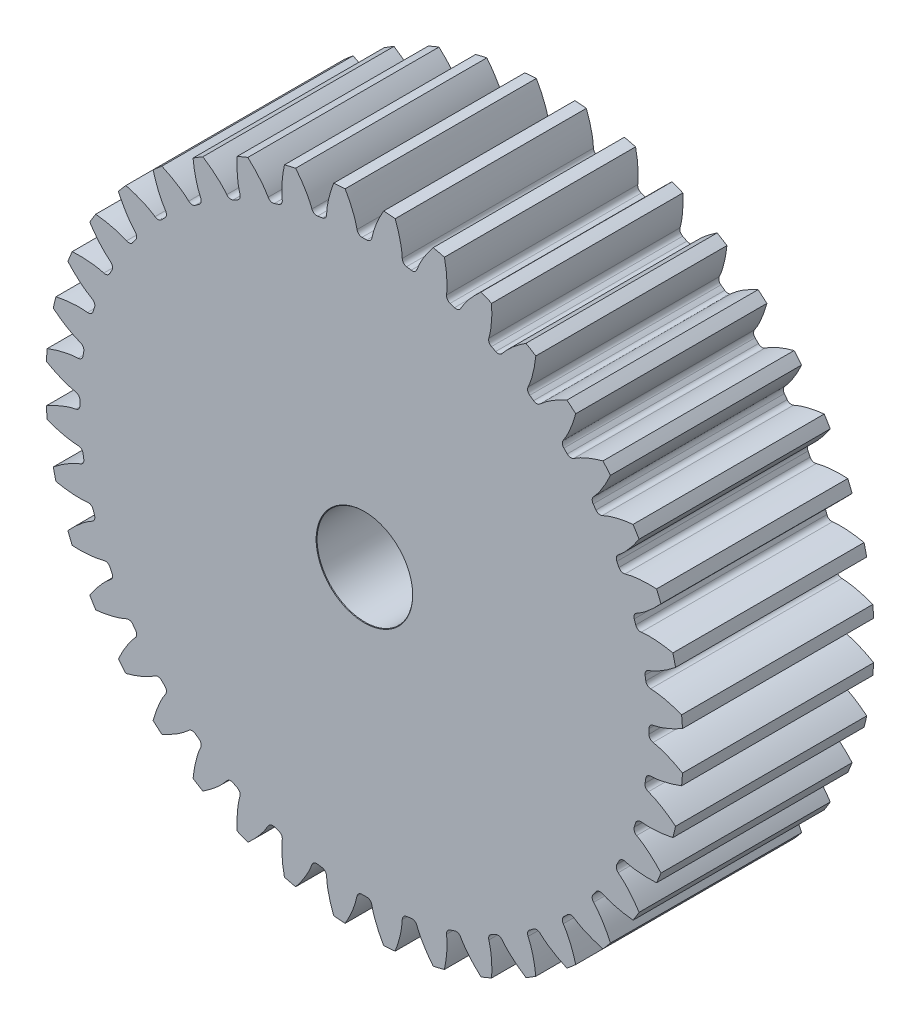
SolidWorks part; units mm, degrees
ref_plane "Front Plane" through (0, 0, 0) normal (0, 0, 1) x (1, 0, 0)
ref_plane "Top Plane" through (0, 0, 0) normal (0, 1, 0) x (1, 0, 0)
ref_plane "Right Plane" through (0, 0, 0) normal (1, 0, 0) x (0, 0, -1)
sketch "Sketch1" plane through (0, 0, 0) normal (0, 0, 1) x (1, 0, 0)
  line L0 (0, 0) -> (0, 15.875) construction
  line L1 (-5.1021, 17.732) -> (5.1021, 14.018) construction
  circle A0 centre (0, 0) radius 14.8828 construction
  circle A1 centre (0, 0) radius 16.6687 construction
  circle A2 centre (0, 0) radius 15.875 construction
  circle A3 centre (0, 0) radius 14.9176 construction
  point P8 (406.4, 0)
  point P13 (508, 0)
  dimension "OD | Outside Diameter" = 33.3375
  dimension "Root Diameter" = 29.7656
  dimension "Gear Pitch Diameter" = 31.75
  dimension "Base Diameter" = 29.8352
  dimension "Pressure Angle" = 20
  dimension "Number of Teeth" = 1016
  dimension "Gear Pitch | Diametral Pitch" = 812.8
sketch "Sketch2" plane through (0, 0, 0) normal (1, 0, 0) x (0, 0, -1)
  line L0 (-5, 0) -> (5, 0) construction
  point P2 (11.6687, 0)
  point P5 (20.0031, 0)
  point P6 (-11.6687, 0)
  dimension "Length" = 10
  dimension "D1" = 16.6687
  dimension "D2" = 25.0031
  dimension "D3" = 16.6687
sketch "Sketch3" plane through (0, 0, 0) normal (0, 0, 1) x (1, 0, 0)
  circle A0 centre (0, 0) radius 16.6687
  circle A1 centre (0, 0) radius 16.6687 construction
extrude "Boss-Extrude1" add sketch "Sketch3" against normal up to vertex (5 mm away) and the other way up to vertex (5 mm away) up to point (0, 0, -5) other way up to point (0, 0, 5)
sketch "Sketch4" plane through (0, 0, 0) normal (0, 0, 1) x (1, 0, 0)
  line L0 (0, 0) -> (14.8784, 0.3626) construction
  line L2 (0, 0) -> (14.8784, -0.3626) construction
  line L4 (14.8784, 0.3626) -> (14.9132, 0.3634)
  line L5 (14.9132, -0.3634) -> (14.8784, -0.3626)
  arc A0 (14.8784, 0.3626) -> (14.8784, -0.3626) centre (0, 0) cw
  arc A3 (16.6383, 1.0067) -> (16.6383, -1.0067) centre (0, 0) cw
  circle A4 centre (0, 0) radius 16.6687 construction
  spline S0 degree 4 poles (14.9132, 0.3634) (14.9159, 0.3635) (14.9236, 0.3639) (14.9381, 0.3649) (14.9618, 0.3671) (14.9919, 0.3706) (15.0308, 0.376) (15.0766, 0.3835) (15.1268, 0.3928) (15.1814, 0.4042) (15.2358, 0.4166) (15.29, 0.4301) (15.3439, 0.4444) (15.4091, 0.4628) (15.4872, 0.4863) (15.5783, 0.516) (15.6814, 0.5524) (15.7862, 0.5921) (15.8891, 0.6335) (15.9927, 0.678) (16.0929, 0.7228) (16.1965, 0.7721) (16.2921, 0.8189) (16.3988, 0.8743) (16.4848, 0.9199) (16.5978, 0.9832) (16.6645, 1.0215) (16.7423, 1.0675) (16.7768, 1.0885) (16.798, 1.1014) knots 0 0 0 0 0 0.005377 0.015084 0.028532 0.04661 0.064855 0.092111 0.119476 0.146842 0.174209 0.201575 0.228941 0.256307 0.307035 0.361767 0.4165 0.471232 0.525964 0.580697 0.635429 0.690161 0.744894 0.799626 0.854358 0.909091 0.954545 1 1 1 1 1 construction
  spline S1 degree 4 poles (14.9132, 0.3634) (14.9159, 0.3635) (14.9236, 0.3639) (14.9381, 0.3649) (14.9618, 0.3671) (14.9919, 0.3706) (15.0308, 0.376) (15.0766, 0.3835) (15.1268, 0.3928) (15.1814, 0.4042) (15.2358, 0.4166) (15.29, 0.4301) (15.3439, 0.4444) (15.4091, 0.4628) (15.4872, 0.4863) (15.5783, 0.516) (15.6814, 0.5524) (15.7862, 0.5921) (15.8891, 0.6335) (15.9927, 0.678) (16.0929, 0.7228) (16.1965, 0.7721) (16.2921, 0.8189) (16.3988, 0.8743) (16.4848, 0.9199) (16.5733, 0.9695) (16.6163, 0.994) (16.6383, 1.0067) knots 0 0 0 0 0 0.005377 0.015084 0.028532 0.04661 0.064855 0.092111 0.119476 0.146842 0.174209 0.201575 0.228941 0.256307 0.307035 0.361767 0.4165 0.471232 0.525964 0.580697 0.635429 0.690161 0.744894 0.799626 0.854358 0.909091 0.909091 0.909091 0.909091 0.909091
  spline S2 degree 4 poles (14.9132, -0.3634) (14.9159, -0.3635) (14.9236, -0.3639) (14.9381, -0.3649) (14.9618, -0.3671) (14.9919, -0.3706) (15.0308, -0.376) (15.0766, -0.3835) (15.1268, -0.3928) (15.1814, -0.4042) (15.2358, -0.4166) (15.29, -0.4301) (15.3439, -0.4444) (15.4091, -0.4628) (15.4872, -0.4863) (15.5783, -0.516) (15.6814, -0.5524) (15.7862, -0.5921) (15.8891, -0.6335) (15.9927, -0.678) (16.0929, -0.7228) (16.1965, -0.7721) (16.2921, -0.8189) (16.3988, -0.8743) (16.4848, -0.9199) (16.5978, -0.9832) (16.6645, -1.0215) (16.7423, -1.0675) (16.7768, -1.0885) (16.798, -1.1014) knots 0 0 0 0 0 0.005377 0.015084 0.028532 0.04661 0.064855 0.092111 0.119476 0.146842 0.174209 0.201575 0.228941 0.256307 0.307035 0.361767 0.4165 0.471232 0.525964 0.580697 0.635429 0.690161 0.744894 0.799626 0.854358 0.909091 0.954545 1 1 1 1 1 construction
  spline S3 degree 4 poles (14.9132, -0.3634) (14.9159, -0.3635) (14.9236, -0.3639) (14.9381, -0.3649) (14.9618, -0.3671) (14.9919, -0.3706) (15.0308, -0.376) (15.0766, -0.3835) (15.1268, -0.3928) (15.1814, -0.4042) (15.2358, -0.4166) (15.29, -0.4301) (15.3439, -0.4444) (15.4091, -0.4628) (15.4872, -0.4863) (15.5783, -0.516) (15.6814, -0.5524) (15.7862, -0.5921) (15.8891, -0.6335) (15.9927, -0.678) (16.0929, -0.7228) (16.1965, -0.7721) (16.2921, -0.8189) (16.3988, -0.8743) (16.4848, -0.9199) (16.5733, -0.9695) (16.6163, -0.994) (16.6383, -1.0067) knots 0 0 0 0 0 0.005377 0.015084 0.028532 0.04661 0.064855 0.092111 0.119476 0.146842 0.174209 0.201575 0.228941 0.256307 0.307035 0.361767 0.4165 0.471232 0.525964 0.580697 0.635429 0.690161 0.744894 0.799626 0.854358 0.909091 0.909091 0.909091 0.909091 0.909091
  dimension "D1" = 29.7656
extrude "Cut-Extrude1" cut sketch "Sketch4" against normal through all both and the other way through all
fillet "Fillet1" radius 0.2663 2 edges at (14.8784, -0.3626, 0) (14.8784, 0.3626, 0)
pattern_circular "CirPattern1" count 40 over 360 about axis through (0, 0, 5) along (0, 0, -1) of "Cut-Extrude1", "Fillet1"
sketch "Sketch5" plane through (0, 0, 5) normal (0, 0, 1) x (1, 0, 0)
  point P0 (0, 0)
hole_wizard "Ø5.0mm Dowel Hole1" positions "Sketch5" profile "Sketch6" hole size "Ø5.0" standard "ANSI Metric" end condition through all
sketch "Sketch6" plane through (0, 0, 5) normal (1, 0, 0) x (0, -1, 0)
  line L0 (0, 0) -> (0, 10)
  line L1 (0, 10) -> (2.5, 10)
  line L2 (2.5, 10) -> (2.5, 0.025)
  line L3 (2.5, 0.025) -> (2.525, 0)
  line L5 (2.525, 0) -> (0, 0)
  line L6 (-2.5, 0.025) -> (-2.525, 0) construction
  line L11 (0, -6.35) -> (0, 107.95) construction
  dimension "Thru Hole Dia." = 5
  dimension "Thru Hole Depth" = 10
  dimension "Near C'Sink Dia." = 5.05
  dimension "Near C'Sink Angle" = 90
equation "\"Root Diameter@Sketch1\"=\"Root Diameter\""
equation "\"OD | Outside Diameter@Sketch1\"=\"Outside Diameter\""
equation "\"D1@CirPattern1\"=\"Number of Teeth\""
equation "\"Diametral Pitch\"=32"
equation "\"Number of Teeth\"= 40"
equation "\"Pressure Angle\"=20"
equation "\"Pitch Diameter\"= \"Number of Teeth\" / \"Diametral Pitch\""
equation "\"Base Diameter\"= \"Pitch Diameter\" * cos ( \"Pressure Angle\" )"
equation "\"Outside Diameter\"= ( \"Number of Teeth\" + 2 ) / \"Diametral Pitch\""
equation "\"Dedendum\"= 1.25 / \"Diametral Pitch\""
equation "\"Root Diameter\"= \"Pitch Diameter\" - ( 2 * \"Dedendum\" )"
equation "\"Pitch Angle\"= 360deg / \"Number of Teeth\""
equation "\"Alpha\"= sqr ( \"Pitch Diameter\" ^ 2 - \"Base Diameter\" ^ 2 ) / \"Base Diameter\" * 180 / PI - \"Pressure Angle\""
equation "\"Beta\"= ( \"Pitch Angle\" / 4 - \"Alpha\" )"
equation "\"Phi\"= sqr ( ( \"Outside Diameter\" / 2 ) ^ 2 - ( \"Base Diameter\" / 2 ) ^ 2 ) / ( \"Base Diameter\" / 2 )"
equation "\"Addendum\"= 1 / \"Diametral Pitch\""
equation "\"WorkingDepth\"= 2 / \"Diametral Pitch\""
equation "\"WholeDepth\"= 2.25 / \"Diametral Pitch\""
equation "\"Clearance\"= 0.25 / \"Diametral Pitch\""
equation "\"ToothThickness\"= ( pi * 2 ) / \"Diametral Pitch\""
equation "\"CircularPitch\"= pi / \"Diametral Pitch\""
equation "\"Number of Teeth@Sketch1\"=\"Number of Teeth\""
equation "\"Gear Pitch | Diametral Pitch@Sketch1\"=\"Diametral Pitch\""
equation "\"Pressure Angle@Sketch1\"=\"Pressure Angle\""
equation "\"Gear Pitch Diameter@Sketch1\"=\"Pitch Diameter\""
equation "\"Base Diameter@Sketch1\"=\"Base Diameter\""
equation "\"Fillet\"= \"Clearance\" * cos ( \"Pressure Angle\" ) * tan ( ( 90 + \"Pressure Angle\" ) / 2 )"
equation "\"D1@Fillet1\"=\"Fillet\""
equation "\"D1@Sketch4\"=if( \"Base Diameter\">\"Root Diameter\",\"Root Diameter\",\"Base Diameter\"-.00001)"
equation "\"D1@Sketch2\"=\"OD | Outside Diameter@Sketch1\"*2*0.5*0.5"
equation "\"D2@Sketch2\"=\"D1@Sketch2\"*1.5"
equation "\"D3@Sketch2\"=\"D1@Sketch2\""
equation "\"Length\"= 1cm"
equation "\"Length@Sketch2\"= \"Length\""
